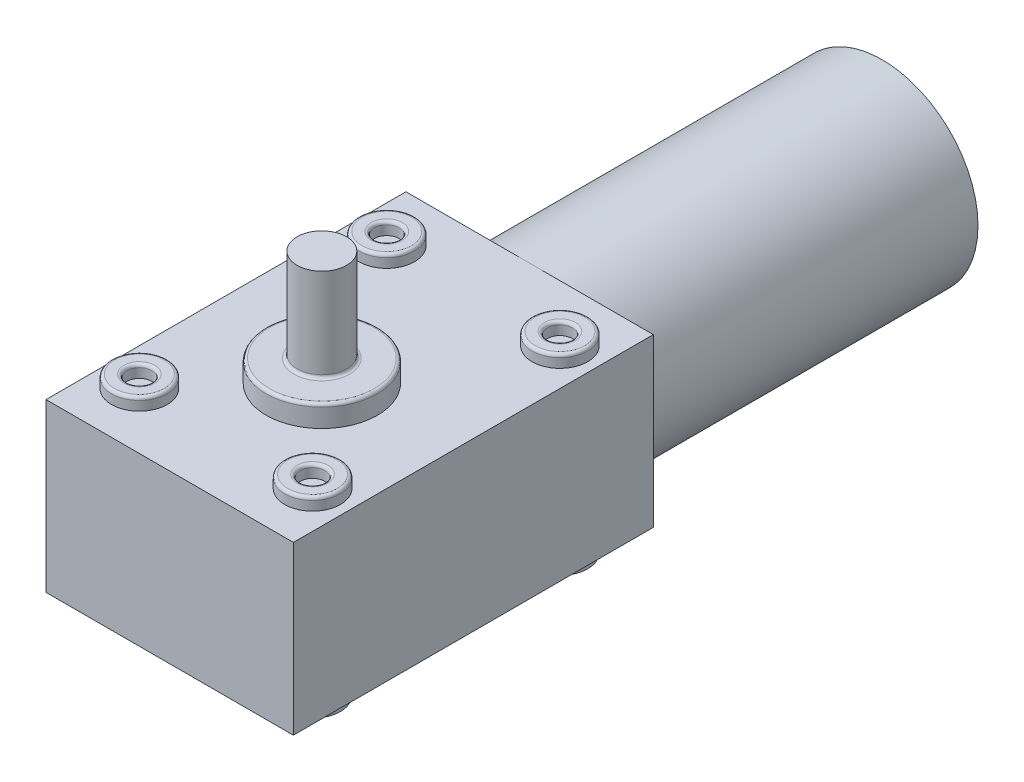
SolidWorks part; units mm, degrees
ref_plane "Front Plane" through (0, 0, 0) normal (0, 0, 1) x (1, 0, 0)
ref_plane "Top Plane" through (0, 0, 0) normal (0, 1, 0) x (1, 0, 0)
ref_plane "Right Plane" through (0, 0, 0) normal (1, 0, 0) x (0, 0, -1)
sketch "Sketch1" plane through (0, 0, 0) normal (0, 0, 1) x (1, 0, 0)
  line L1 (-20, -13.5) -> (20, -13.5)
  line L2 (-20, -13.5) -> (-20, 13.5)
  line L3 (-20, 13.5) -> (20, 13.5)
  line L4 (20, -13.5) -> (20, 13.5)
  line L5 (-20, -13.5) -> (20, 13.5) construction
  line L6 (-20, 13.5) -> (20, -13.5) construction
  point P0 (0, 0)
  dimension "D1" = 40
  dimension "D2" = 27
extrude "Boss-Extrude1" add sketch "Sketch1" along normal blind 58.2
sketch "Sketch3" plane through (0, 0, 0) normal (0, 0, 1) x (1, 0, 0)
  line L0 (20, 13.5) -> (-20, 13.5) construction
  circle A0 centre (0, -2) radius 15.5
  dimension "D1" = 31
extrude "Boss-Extrude2" add sketch "Sketch3" against normal blind 57
sketch "Sketch4" plane through (0, 13.5, 0) normal (0, 1, 0) x (1, 0, 0)
  line L0 (20, -58.2) -> (20, 0) construction
  line L2 (14, -9.1) -> (-14, -9.1) construction
  line L3 (-14, -9.1) -> (-14, -49.1) construction
  line L4 (-14, -49.1) -> (14, -49.1) construction
  line L5 (14, -49.1) -> (14, -9.1) construction
  line L6 (14, -9.1) -> (-14, -9.1) construction
  circle A0 centre (14, -9.1) radius 4.5
  circle A1 centre (-14, -9.1) radius 4.5
  circle A2 centre (14, -49.1) radius 4.5
  circle A3 centre (-14, -49.1) radius 4.5
  circle A4 centre (-14, -9.1) radius 2
  circle A5 centre (14, -9.1) radius 2
  circle A6 centre (14, -49.1) radius 2
  circle A7 centre (-14, -49.1) radius 2
  point P8 (0, -9.1)
  point P9 (14, -29.1)
  point P12 (20, -29.1)
  dimension "D1" = 9
  dimension "D4" = 4
  dimension "D2" = 28
  dimension "D3" = 28
  dimension "D5" = 40
extrude "Boss-Extrude3" add sketch "Sketch4" along normal blind 2
sketch "Sketch5" plane through (0, 13.5, 0) normal (0, 1, 0) x (1, 0, 0)
  circle A0 centre (0, -33.6) radius 9
  circle A1 centre (-14, -49.1) radius 4.5 construction
  dimension "D1" = 18
  dimension "D2" = 15.5
extrude "Boss-Extrude4" add sketch "Sketch5" along normal blind 3.5
sketch "Sketch6" plane through (0, 17, 0) normal (0, 1, 0) x (1, 0, 0)
  circle A0 centre (0, -33.6) radius 4
  dimension "D1" = 8
extrude "Boss-Extrude5" add sketch "Sketch6" along normal blind 15
fillet "Fillet1" radius 0.5 10 edges at (0, 17, 42.6) (0, 17, 37.6) (-14, 15.5, 51.1) (-14, 15.5, 53.6) (14, 15.5, 51.1) (14, 15.5, 53.6) (-14, 15.5, 11.1) (-14, 15.5, 13.6) (14, 15.5, 11.1) (14, 15.5, 13.6)
mirror "Mirror2" about plane through (0, 0, 0) normal (0, 1, 0) of "Boss-Extrude4", "Boss-Extrude3"
